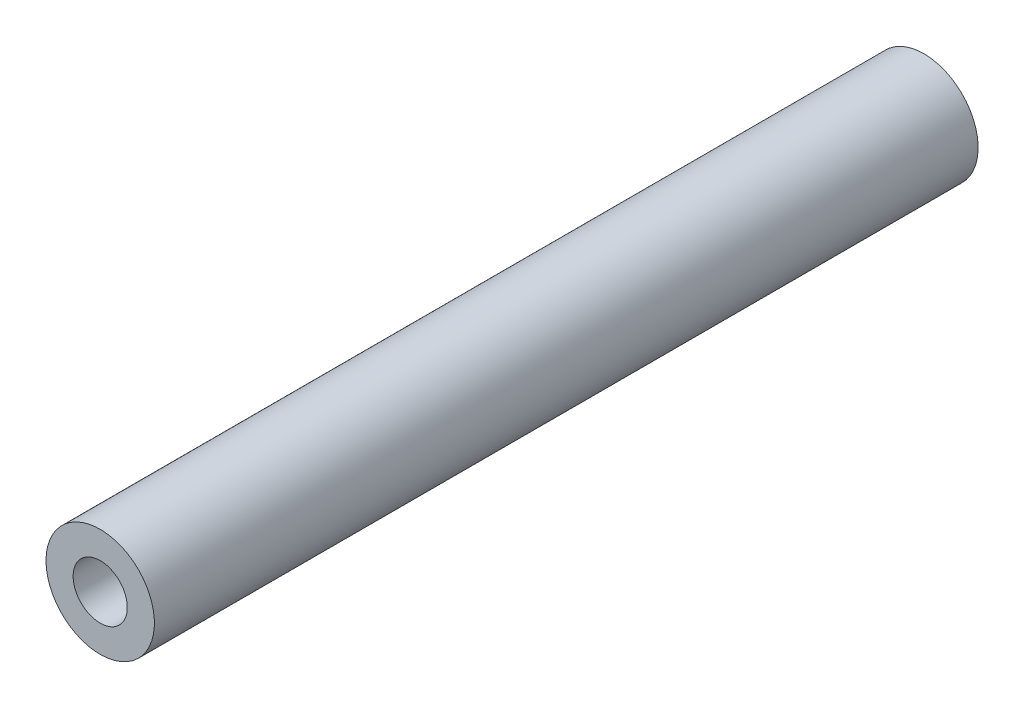
SolidWorks part; units mm, degrees
ref_plane "Front Plane" through (0, 0, 0) normal (0, 0, 1) x (1, 0, 0)
ref_plane "Top Plane" through (0, 0, 0) normal (0, 1, 0) x (1, 0, 0)
ref_plane "Right Plane" through (0, 0, 0) normal (1, 0, 0) x (0, 0, -1)
sketch "Sketch1" plane through (0, 0, 0) normal (0, 0, 1) x (1, 0, 0)
  circle A0 centre (0, 0) radius 3.175
  circle A1 centre (0, 0) radius 6.35
  dimension "D1" = 6.35
  dimension "D2" = 12.7
extrude "Boss-Extrude1" add sketch "Sketch1" along normal blind 96.52
